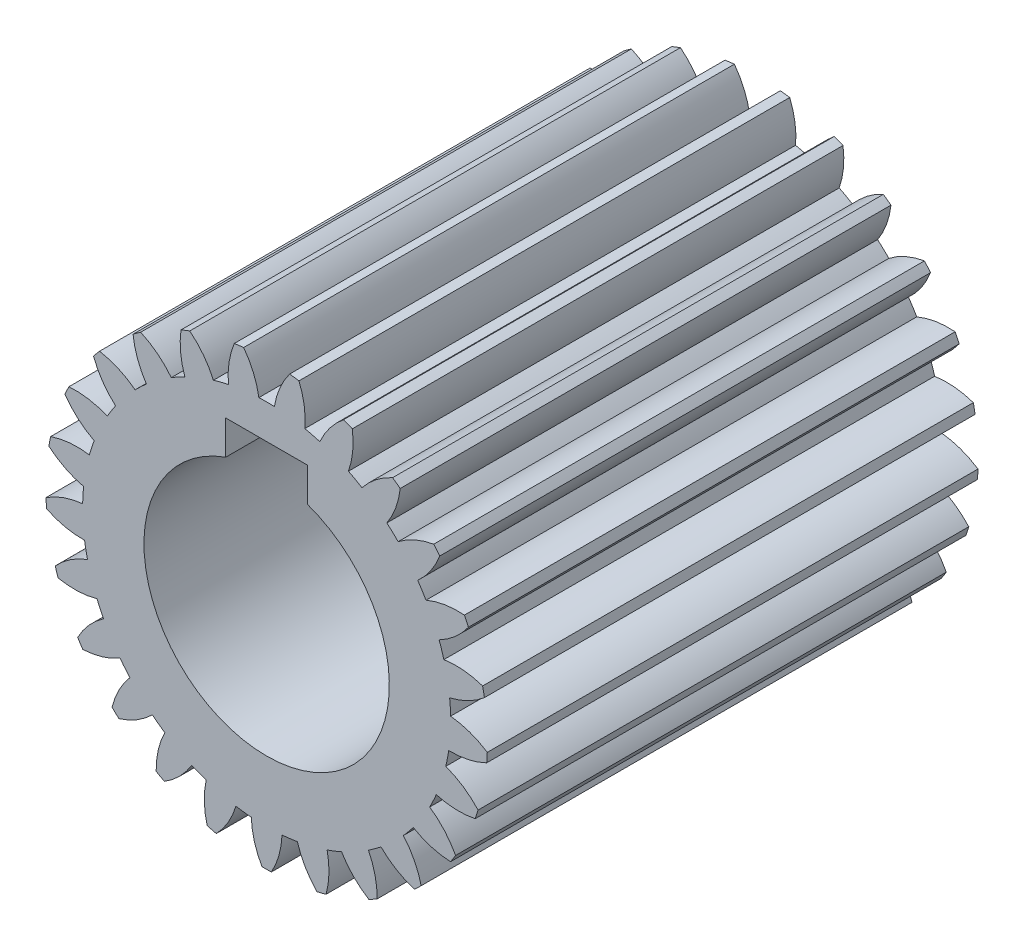
SolidWorks part; units mm, degrees
ref_plane "前视基准面" through (0, 0, 0) normal (0, 0, 1) x (1, 0, 0)
ref_plane "上视基准面" through (0, 0, 0) normal (0, 1, 0) x (1, 0, 0)
ref_plane "右视基准面" through (0, 0, 0) normal (1, 0, 0) x (0, 0, -1)
sketch "Model" plane through (0, 0, 0) normal (0, 0, 1) x (1, 0, 0)
  line L0 (5, 14.1421) -> (5, 18.3)
  line L1 (-5, 18.3) -> (-5, 14.1421)
  line L2 (5, 18.3) -> (-5, 18.3)
  arc A0 (-26.6237, 4.4923) -> (-22.3753, 2.3558) centre (-20.1355, 12.1017) ccw
  arc A1 (-22.3753, 2.3558) -> (-22.4941, 0.4672) centre (0, 0) ccw
  arc A2 (-22.4941, 0.4672) -> (-26.9768, -1.12) centre (-21.4935, -9.4826) ccw
  arc A3 (-26.9768, -1.12) -> (-26.9044, -2.2699) centre (0, 0) ccw
  arc A4 (-26.9044, -2.2699) -> (-22.2582, -3.2828) centre (-22.5125, 6.714) ccw
  arc A5 (-22.2582, -3.2828) -> (-21.9036, -5.1416) centre (0, 0) ccw
  arc A6 (-21.9036, -5.1416) -> (-25.8507, -7.7937) centre (-18.46, -14.5299) ccw
  arc A7 (-25.8507, -7.7937) -> (-25.4947, -8.8895) centre (0, 0) ccw
  arc A8 (-25.4947, -8.8895) -> (-20.7425, -8.715) centre (-23.4749, 0.9044) ccw
  arc A9 (-20.7425, -8.715) -> (-19.9368, -10.4272) centre (0, 0) ccw
  arc A10 (-19.9368, -10.4272) -> (-23.1004, -13.9776) centre (-14.2666, -18.6642) ccw
  arc A11 (-23.1004, -13.9776) -> (-22.483, -14.9504) centre (0, 0) ccw
  arc A12 (-22.483, -14.9504) -> (-17.9235, -13.5997) centre (-22.9623, -4.9619) ccw
  arc A13 (-17.9235, -13.5997) -> (-16.7173, -15.0577) centre (0, 0) ccw
  arc A14 (-16.7173, -15.0577) -> (-18.8985, -19.2833) centre (-9.1768, -21.6258) ccw
  arc A15 (-18.8985, -19.2833) -> (-18.0586, -20.072) centre (0, 0) ccw
  arc A16 (-18.0586, -20.072) -> (-13.9783, -17.6298) centre (-21.0069, -10.5165) ccw
  arc A17 (-13.9783, -17.6298) -> (-12.4474, -18.7421) centre (0, 0) ccw
  arc A18 (-12.4474, -18.7421) -> (-13.5092, -23.3774) centre (-3.5103, -23.2286) ccw
  arc A19 (-13.5092, -23.3774) -> (-12.4996, -23.9324) centre (0, 0) ccw
  arc A20 (-12.4996, -23.9324) -> (-9.1548, -20.5522) centre (-17.7316, -15.4104) ccw
  arc A21 (-9.1548, -20.5522) -> (-7.3954, -21.2488) centre (0, 0) ccw
  arc A22 (-7.3954, -21.2488) -> (-7.2711, -26.0025) centre (2.3767, -23.3718) ccw
  arc A23 (-7.2711, -26.0025) -> (-6.1551, -26.2891) centre (0, 0) ccw
  arc A24 (-6.1551, -26.2891) -> (-3.7561, -22.1833) centre (-13.3421, -19.3359) ccw
  arc A25 (-3.7561, -22.1833) -> (-1.8787, -22.4204) centre (0, 0) ccw
  arc A26 (-1.8787, -22.4204) -> (-0.5761, -26.9939) centre (8.1143, -22.0465) ccw
  arc A27 (-0.5761, -26.9939) -> (0.5761, -26.9939) centre (0, 0) ccw
  arc A28 (0.5761, -26.9939) -> (1.8787, -22.4204) centre (-8.1143, -22.0465) ccw
  arc A29 (1.8787, -22.4204) -> (3.7561, -22.1833) centre (0, 0) ccw
  arc A30 (3.7561, -22.1833) -> (6.1551, -26.2891) centre (13.3421, -19.3359) ccw
  arc A31 (6.1551, -26.2891) -> (7.2711, -26.0025) centre (0, 0) ccw
  arc A32 (7.2711, -26.0025) -> (7.3954, -21.2488) centre (-2.3767, -23.3718) ccw
  arc A33 (7.3954, -21.2488) -> (9.1548, -20.5522) centre (0, 0) ccw
  arc A34 (9.1548, -20.5522) -> (12.4996, -23.9324) centre (17.7316, -15.4104) ccw
  arc A35 (12.4996, -23.9324) -> (13.5092, -23.3774) centre (0, 0) ccw
  arc A36 (13.5092, -23.3774) -> (12.4474, -18.7421) centre (3.5103, -23.2286) ccw
  arc A37 (12.4474, -18.7421) -> (13.9783, -17.6298) centre (0, 0) ccw
  arc A38 (13.9783, -17.6298) -> (18.0586, -20.072) centre (21.0069, -10.5165) ccw
  arc A39 (18.0586, -20.072) -> (18.8985, -19.2833) centre (0, 0) ccw
  arc A40 (18.8985, -19.2833) -> (16.7173, -15.0577) centre (9.1768, -21.6258) ccw
  arc A41 (16.7173, -15.0577) -> (17.9235, -13.5997) centre (0, 0) ccw
  arc A42 (17.9235, -13.5997) -> (22.483, -14.9504) centre (22.9623, -4.9619) ccw
  arc A43 (22.483, -14.9504) -> (23.1004, -13.9776) centre (0, 0) ccw
  arc A44 (23.1004, -13.9776) -> (19.9368, -10.4272) centre (14.2666, -18.6642) ccw
  arc A45 (19.9368, -10.4272) -> (20.7425, -8.715) centre (0, 0) ccw
  arc A46 (20.7425, -8.715) -> (25.4947, -8.8895) centre (23.4749, 0.9044) ccw
  arc A47 (25.4947, -8.8895) -> (25.8507, -7.7937) centre (0, 0) ccw
  arc A48 (25.8507, -7.7937) -> (21.9036, -5.1416) centre (18.46, -14.5299) ccw
  arc A49 (21.9036, -5.1416) -> (22.2582, -3.2828) centre (0, 0) ccw
  arc A50 (22.2582, -3.2828) -> (26.9044, -2.2699) centre (22.5125, 6.714) ccw
  arc A51 (26.9044, -2.2699) -> (26.9768, -1.12) centre (0, 0) ccw
  arc A52 (26.9768, -1.12) -> (22.4941, 0.4672) centre (21.4935, -9.4826) ccw
  arc A53 (22.4941, 0.4672) -> (22.3753, 2.3558) centre (0, 0) ccw
  arc A54 (22.3753, 2.3558) -> (26.6237, 4.4923) centre (20.1355, 12.1017) ccw
  arc A55 (26.6237, 4.4923) -> (26.4078, 5.624) centre (0, 0) ccw
  arc A56 (26.4078, 5.624) -> (21.6713, 6.0466) centre (23.1764, -3.8395) ccw
  arc A57 (21.6713, 6.0466) -> (21.0865, 7.8463) centre (0, 0) ccw
  arc A58 (21.0865, 7.8463) -> (24.6701, 10.9722) centre (16.4933, 16.729) ccw
  arc A59 (24.6701, 10.9722) -> (24.1795, 12.0147) centre (0, 0) ccw
  arc A60 (24.1795, 12.0147) -> (19.4867, 11.246) centre (23.4031, 2.0449) ccw
  arc A61 (19.4867, 11.246) -> (18.4728, 12.8438) centre (0, 0) ccw
  arc A62 (18.4728, 12.8438) -> (21.1663, 16.7626) centre (11.8148, 20.3051) ccw
  arc A63 (21.1663, 16.7626) -> (20.4319, 17.6504) centre (0, 0) ccw
  arc A64 (20.4319, 17.6504) -> (16.0777, 15.7389) centre (22.1594, 7.8008) ccw
  arc A65 (16.0777, 15.7389) -> (14.6983, 17.0342) centre (0, 0) ccw
  arc A66 (14.6983, 17.0342) -> (16.3327, 21.4999) centre (6.394, 22.6054) ccw
  arc A67 (16.3327, 21.4999) -> (15.4005, 22.1771) centre (0, 0) ccw
  arc A68 (15.4005, 22.1771) -> (11.6585, 19.2428) centre (19.5232, 13.0665) ccw
  arc A69 (11.6585, 19.2428) -> (10.0003, 20.1544) centre (0, 0) ccw
  arc A70 (10.0003, 20.1544) -> (10.4727, 24.8862) centre (0.5713, 23.4854) ccw
  arc A71 (10.4727, 24.8862) -> (9.4015, 25.3103) centre (0, 0) ccw
  arc A72 (9.4015, 25.3103) -> (6.5068, 21.5376) centre (15.6604, 17.5112) ccw
  arc A73 (6.5068, 21.5376) -> (4.6739, 22.0082) centre (0, 0) ccw
  arc A74 (4.6739, 22.0082) -> (3.9548, 26.7088) centre (-5.2872, 22.8896) ccw
  arc A75 (3.9548, 26.7088) -> (2.8117, 26.8532) centre (0, 0) ccw
  arc A76 (2.8117, 26.8532) -> (0.9462, 22.4791) centre (10.8135, 20.8556) ccw
  arc A77 (0.9462, 22.4791) -> (-0.9462, 22.4791) centre (0, 0) ccw
  arc A78 (-0.9462, 22.4791) -> (-2.8117, 26.8532) centre (-10.8135, 20.8556) ccw
  arc A79 (-2.8117, 26.8532) -> (-3.9548, 26.7088) centre (0, 0) ccw
  arc A80 (-3.9548, 26.7088) -> (-4.6739, 22.0082) centre (5.2872, 22.8896) ccw
  arc A81 (-4.6739, 22.0082) -> (-6.5068, 21.5376) centre (0, 0) ccw
  arc A82 (-6.5068, 21.5376) -> (-9.4015, 25.3103) centre (-15.6604, 17.5112) ccw
  arc A83 (-9.4015, 25.3103) -> (-10.4727, 24.8862) centre (0, 0) ccw
  arc A84 (-10.4727, 24.8862) -> (-10.0003, 20.1544) centre (-0.5713, 23.4854) ccw
  arc A85 (-10.0003, 20.1544) -> (-11.6585, 19.2428) centre (0, 0) ccw
  arc A86 (-11.6585, 19.2428) -> (-15.4005, 22.1771) centre (-19.5232, 13.0665) ccw
  arc A87 (-15.4005, 22.1771) -> (-16.3327, 21.4999) centre (0, 0) ccw
  arc A88 (-16.3327, 21.4999) -> (-14.6983, 17.0342) centre (-6.394, 22.6054) ccw
  arc A89 (-14.6983, 17.0342) -> (-16.0777, 15.7389) centre (0, 0) ccw
  arc A90 (-16.0777, 15.7389) -> (-20.4319, 17.6504) centre (-22.1594, 7.8008) ccw
  arc A91 (-20.4319, 17.6504) -> (-21.1663, 16.7626) centre (0, 0) ccw
  arc A92 (-21.1663, 16.7626) -> (-18.4728, 12.8438) centre (-11.8148, 20.3051) ccw
  arc A93 (-18.4728, 12.8438) -> (-19.4867, 11.246) centre (0, 0) ccw
  arc A94 (-19.4867, 11.246) -> (-24.1795, 12.0147) centre (-23.4031, 2.0449) ccw
  arc A95 (-24.1795, 12.0147) -> (-24.6701, 10.9722) centre (0, 0) ccw
  arc A96 (-24.6701, 10.9722) -> (-21.0865, 7.8463) centre (-16.4933, 16.729) ccw
  arc A97 (-21.0865, 7.8463) -> (-21.6713, 6.0466) centre (0, 0) ccw
  arc A98 (-21.6713, 6.0466) -> (-26.4078, 5.624) centre (-23.1764, -3.8395) ccw
  arc A99 (-26.4078, 5.624) -> (-26.6237, 4.4923) centre (0, 0) ccw
  arc A100 (-5, 14.1421) -> (5, 14.1421) centre (0, 0) ccw
extrude "凸台-拉伸1" add sketch "Model" along normal blind 60 contours A97 A98 A99 A0 A1 A2 A3 A4 A5 A6 A7 A8 A9 A10 A11 A12 A13 A14 A15 A16 A17 A18 A19 A20 A21 A22 A23 A24 A25 A26 A27 A28 A29 A30 A31 A32 A33 A34 A35 A36 A37 A38 A39 A40 A41 A42 A43 A44 A45 A46 A47 A48 A49 A50 A51 A52 A53 A54 A55 A56 A57 A58 A59 A60 A61 A62 A63 A64 A65 A66 A67 A68 A69 A70 A71 A72 A73 A74 A75 A76 A77 A78 A79 A80 A81 A82 A83 A84 A85 A86 A87 A88 A89 A90 A91 A92 A93 A94 A95 A96
